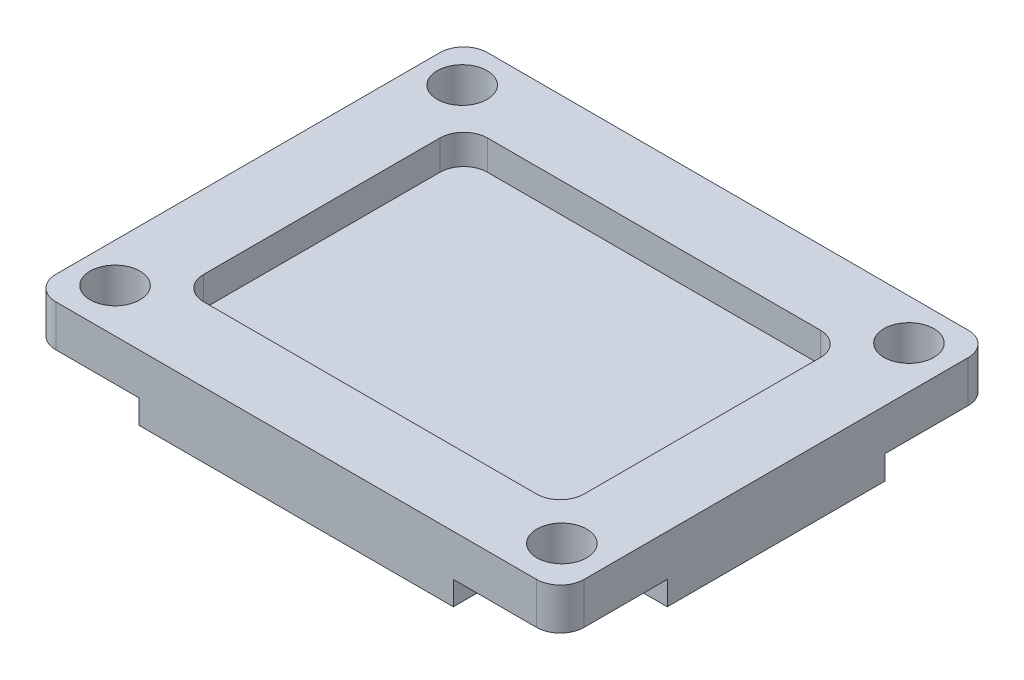
SolidWorks part; units mm, degrees
ref_plane "Спереди" through (0, 0, 0) normal (0, 0, 1) x (1, 0, 0)
ref_plane "Сверху" through (0, 0, 0) normal (0, 1, 0) x (1, 0, 0)
ref_plane "Справа" through (0, 0, 0) normal (1, 0, 0) x (0, 0, -1)
sketch "Эскиз1" plane through (0, 0, 0) normal (0, 1, 0) x (1, 0, 0)
  line L0 (0, 36.32) -> (44.45, 36.32)
  line L1 (0, 0) -> (44.45, 0)
  line L2 (44.45, 36.32) -> (44.45, 0)
  line L3 (0, 36.32) -> (0, 0)
  dimension "D1" = 44.45
  dimension "D2" = 36.32
extrude "Бобышка-Вытянуть1" add sketch "Эскиз1" along normal blind 5.5
sketch "Эскиз2" plane through (0, 5.5, 0) normal (0, 1, 0) x (1, 0, 0)
  line L0 (0, 36.32) -> (0, 0) construction
  line L1 (44.45, 36.32) -> (0, 36.32) construction
  line L2 (44.45, 0) -> (44.45, 36.32) construction
  line L3 (0, 0) -> (44.45, 0) construction
  circle A0 centre (3.302, 32.891) radius 2.1
  circle A1 centre (40.894, 32.89) radius 2.1
  circle A2 centre (40.894, 3.683) radius 2.1
  circle A3 centre (3.302, 3.683) radius 2.1
  dimension "D1" = 4.2
  dimension "D4" = 4.2
  dimension "D5" = 4.2
  dimension "D6" = 4.2
  dimension "D2" = 3.302
  dimension "D3" = 3.429
  dimension "D7" = 3.43
  dimension "D8" = 3.556
  dimension "D9" = 3.556
  dimension "D10" = 3.683
  dimension "D11" = 3.302
  dimension "D12" = 3.683
extrude "Вырез-Вытянуть1" cut sketch "Эскиз2" against normal through all
fillet "Скругление2" radius 2 4 edges at (0, 2.75, -36.32) (44.45, 2.75, -36.32) (44.45, 2.75, 0) (0, 2.75, 0)
sketch "Эскиз5" plane through (0, 0, 0) normal (0, -1, 0) x (1, 0, 0)
  line L0 (0, -34.32) -> (0, -2) construction
  line L1 (6.22, -30.1) -> (38.23, -30.1)
  line L2 (6.22, -30.1) -> (6.22, -6.22)
  line L3 (6.22, -6.22) -> (38.23, -6.22)
  line L4 (38.23, -30.1) -> (38.23, -6.22)
  line L5 (44.45, -2) -> (44.45, -34.32) construction
  line L6 (2, 0) -> (42.45, 0) construction
  line L7 (42.45, -36.32) -> (2, -36.32) construction
  point P6 (0, -18.16)
  dimension "D1" = 6.22
  dimension "D2" = 6.22
  dimension "D3" = 6.22
  dimension "D4" = 6.22
extrude "Вырез-Вытянуть2" cut sketch "Эскиз5" along normal blind 2.5 from surface at -5.5 starting at face at (3.302, 5.5, -1.583)
fillet "Скругление3" radius 2 4 edges at (38.23, 4.25, -30.1) (6.22, 4.25, -30.1) (6.22, 4.25, -6.22) (38.23, 4.25, -6.22)
sketch "Эскиз6" plane through (0, 0, 0) normal (0, -1, 0) x (1, 0, 0)
  line L0 (0, -34.32) -> (0, -2) construction
  line L1 (0, -9) -> (9, -9)
  line L2 (0, -9) -> (0, 0)
  line L3 (0, 0) -> (9, 0)
  line L4 (9, -9) -> (9, 0)
  line L5 (2, 0) -> (42.45, 0) construction
  line L6 (44.45, -2) -> (44.45, -34.32) construction
  line L7 (35.45, 0) -> (44.45, 0)
  line L8 (35.45, 0) -> (35.45, -9)
  line L9 (35.45, -9) -> (44.45, -9)
  line L10 (44.45, 0) -> (44.45, -9)
  line L11 (42.45, -36.32) -> (2, -36.32) construction
  line L12 (44.45, -27.32) -> (35.45, -27.32)
  line L13 (44.45, -27.32) -> (44.45, -36.32)
  line L14 (44.45, -36.32) -> (35.45, -36.32)
  line L15 (35.45, -27.32) -> (35.45, -36.32)
  line L17 (0, -27.32) -> (9, -27.32)
  line L18 (0, -27.32) -> (0, -36.32)
  line L19 (0, -36.32) -> (9, -36.32)
  line L20 (9, -27.32) -> (9, -36.32)
  dimension "D1" = 9
  dimension "D2" = 9
  dimension "D3" = 9
  dimension "D4" = 9
  dimension "D5" = 9
  dimension "D6" = 9
  dimension "D7" = 9
  dimension "D8" = 9
extrude "Вырез-Вытянуть3" cut sketch "Эскиз6" against normal blind 2
